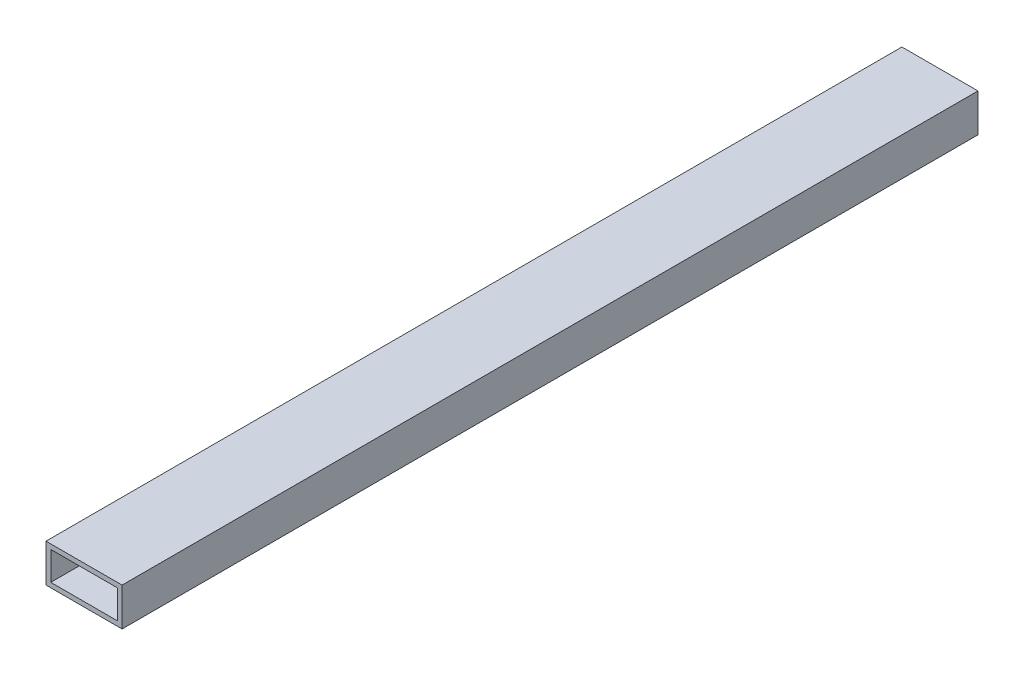
SolidWorks part; units mm, degrees
material "6061-T6 (SS)"
ref_plane "Front" through (0, 0, 0) normal (0, 0, 1) x (1, 0, 0)
ref_plane "Top" through (0, 0, 0) normal (0, 1, 0) x (1, 0, 0)
ref_plane "Right" through (0, 0, 0) normal (1, 0, 0) x (0, 0, -1)
sketch "Sketch1" plane through (0, 0, 0) normal (0, 0, 1) x (1, 0, 0)
  line L0 (-17.5, -7.5) -> (-17.5, 7.5)
  line L1 (-20, -10) -> (20, -10)
  line L2 (-20, -10) -> (-20, 10)
  line L3 (-20, 10) -> (20, 10)
  line L4 (20, -10) -> (20, 10)
  line L5 (-20, -10) -> (20, 10) construction
  line L6 (-20, 10) -> (20, -10) construction
  line L7 (-17.5, 7.5) -> (17.5, 7.5)
  line L8 (17.5, -7.5) -> (17.5, 7.5)
  line L9 (-17.5, -7.5) -> (17.5, -7.5)
  point P0 (0, 0)
  dimension "D2" = 40
  dimension "D3" = 20
  dimension "D1" = 2.5
extrude "Boss-Extrude1" add sketch "Sketch1" along normal mid plane 450
